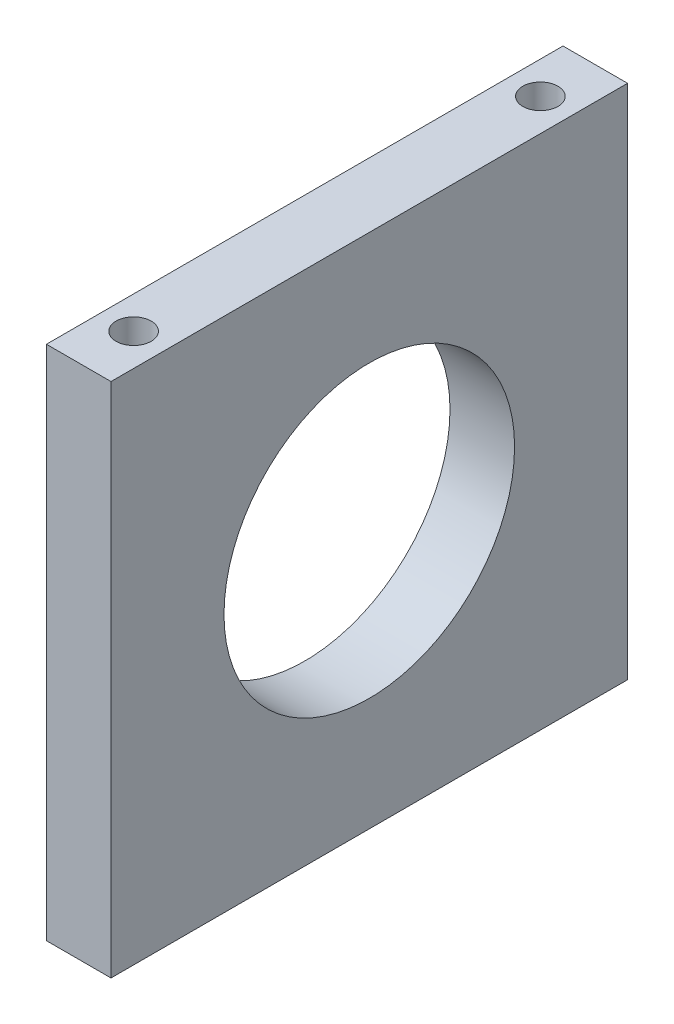
SolidWorks part; units mm, degrees
ref_plane "Front Plane" through (0, 0, 0) normal (0, 0, 1) x (1, 0, 0)
ref_plane "Top Plane" through (0, 0, 0) normal (0, 1, 0) x (1, 0, 0)
ref_plane "Right Plane" through (0, 0, 0) normal (1, 0, 0) x (0, 0, -1)
sketch "Sketch1" plane through (0, 0, 0) normal (1, 0, 0) x (0, 0, -1)
  line L0 (-25.4, 0.3969) -> (25.4, 0.3969) construction
  line L1 (-25.4, -25.4) -> (25.4, -25.4)
  line L2 (-25.4, -25.4) -> (-25.4, 25.4)
  line L3 (-25.4, 25.4) -> (25.4, 25.4)
  line L4 (25.4, -25.4) -> (25.4, 25.4)
  line L5 (-25.4, -25.4) -> (25.4, 25.4) construction
  line L6 (-25.4, 25.4) -> (25.4, -25.4) construction
  line L7 (-25.4, 0.3969) -> (-25.4, -0.3969)
  line L8 (25.4, 0.3969) -> (25.4, -0.3969)
  line L9 (-25.4, -0.3969) -> (25.4, -0.3969) construction
  line L10 (-25.4, 0.3969) -> (25.4, -0.3969) construction
  line L11 (25.4, 0.3969) -> (-25.4, -0.3969) construction
  circle A0 centre (0, 0) radius 14.2875
  circle A1 centre (0, 0) radius 14.6875 construction
  point P0 (0, 0)
  dimension "D1" = 28.575
  dimension "D2" = 0.4
  dimension "D3" = 50.8
  dimension "D4" = 0.7937
extrude "Boss-Extrude1" add sketch "Sketch1" along normal mid plane 6.35 contours A1 L0 L4 L3 L2 | A1 L9 L2 L1 L4
sketch "Sketch3" plane through (0, 25.4, 0) normal (0, 1, 0) x (1, 0, 0)
  line L0 (3.175, -25.4) -> (-3.175, -25.4) construction
  line L1 (3.175, 25.4) -> (-3.175, 25.4) construction
  point P0 (0, 20.0025)
  point P1 (0, -20.0025)
  dimension "D1" = 5.3975
  dimension "D2" = 5.3975
hole_wizard "#18 (0.1695) Diameter Hole2" positions "3DSketch1" profile "Sketch4" hole size "#18" standard "ANSI Inch"
sketch3d "3DSketch1"
  point P0 (0, 25.4, 20.0025)
  point P3 (0, 25.4, -20.0025)
sketch "Sketch4" plane through (0, 25.4, 20.0025) normal (1, 0, 0) x (0, 0, 1)
  line L0 (0, 0) -> (0, 50.8)
  line L1 (0, 50.8) -> (2.1526, 50.8)
  line L2 (2.1526, 50.8) -> (2.1526, 0)
  line L5 (2.1526, 0) -> (0, 0)
  line L11 (0, -6.35) -> (0, 107.95) construction
  dimension "Thru Hole Dia." = 4.3053
  dimension "Thru Hole Depth" = 50.8
hole_wizard "#29 (0.136) Diameter Hole1" positions "3DSketch2" profile "Sketch5" hole size "#29" standard "ANSI Inch"
sketch3d "3DSketch2"
  point P0 (0, 25.4, 20.0025)
  point P3 (0, 25.4, -20.0025)
sketch "Sketch5" plane through (0, 25.4, 20.0025) normal (1, 0, 0) x (0, 0, 1)
  line L0 (0, 0) -> (0, 39.1378)
  line L1 (0, 39.1378) -> (1.7272, 38.1)
  line L2 (1.7272, 38.1) -> (1.7272, 0)
  line L5 (1.7272, 0) -> (0, 0)
  line L10 (0, 39.1378) -> (-1.7272, 38.1) construction
  line L11 (0, -6.35) -> (0, 107.95) construction
  dimension "Hole Dia." = 3.4544
  dimension "Hole Depth" = 38.1
  dimension "Drill Angle" = 118
